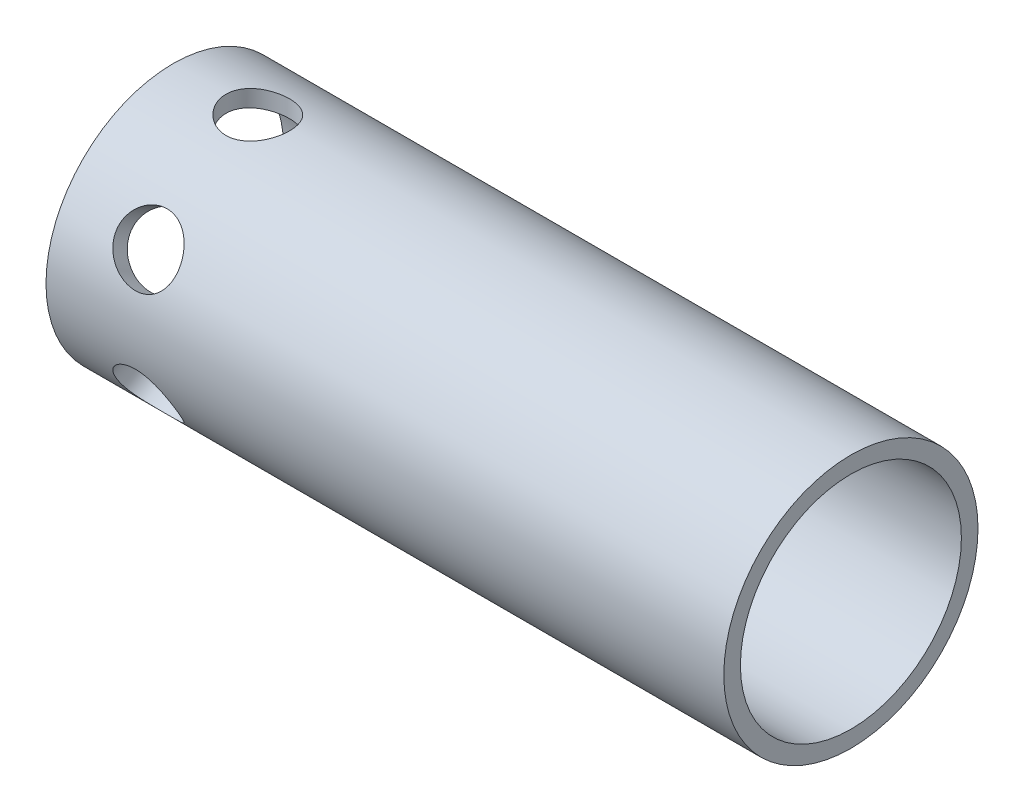
SolidWorks part; units mm, degrees
ref_plane "Front" through (0, 0, 0) normal (0, 0, 1) x (1, 0, 0)
ref_plane "Top" through (0, 0, 0) normal (0, 1, 0) x (1, 0, 0)
ref_plane "Right" through (0, 0, 0) normal (1, 0, 0) x (0, 0, -1)
sketch "Sketch1" plane through (0, 0, 0) normal (1, 0, 0) x (0, 0, -1)
  circle A0 centre (0, 0) radius 9.525
  circle A1 centre (0, 0) radius 8.2804
  point P4 (9.525, 0)
  point P5 (8.2804, 0)
  dimension "OD" = 19.05
  dimension "ID" = 16.5608
  dimension "Wall" = 1.2446
extrude "Extrude1" add sketch "Sketch1" along normal mid plane 50.8
sketch "Sketch2" plane through (0, 0, 0) normal (0, 1, 0) x (1, 0, 0)
  line L0 (-25.4, 9.525) -> (-25.4, -9.525) construction
  circle A0 centre (-19.05, 0) radius 2.3813
  dimension "D2" = 4.7625
  dimension "D1" = 6.35
extrude "Cut-Extrude1" cut sketch "Sketch2" against normal through all both and the other way through all
pattern_circular "CirPattern1" count 3 every 60 about axis through (25.4, 0, 0) along (-1, 0, 0) of "Cut-Extrude1"
